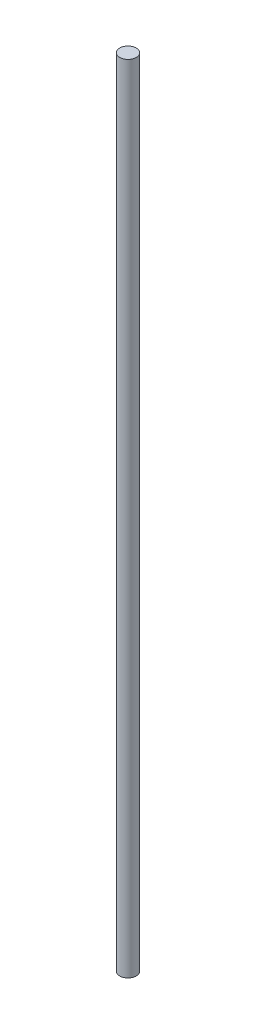
SolidWorks part; units mm, degrees
ref_plane "Alzado" through (0, 0, 0) normal (0, 0, 1) x (1, 0, 0)
ref_plane "Planta" through (0, 0, 0) normal (0, 1, 0) x (1, 0, 0)
ref_plane "Vista lateral" through (0, 0, 0) normal (1, 0, 0) x (0, 0, -1)
sketch "Croquis1" plane through (0, 0, 0) normal (0, 1, 0) x (1, 0, 0)
  circle A0 centre (-8.5683, 5.4182) radius 4
extrude "Saliente-Extruir1" add sketch "Croquis1" along normal blind 386.5
